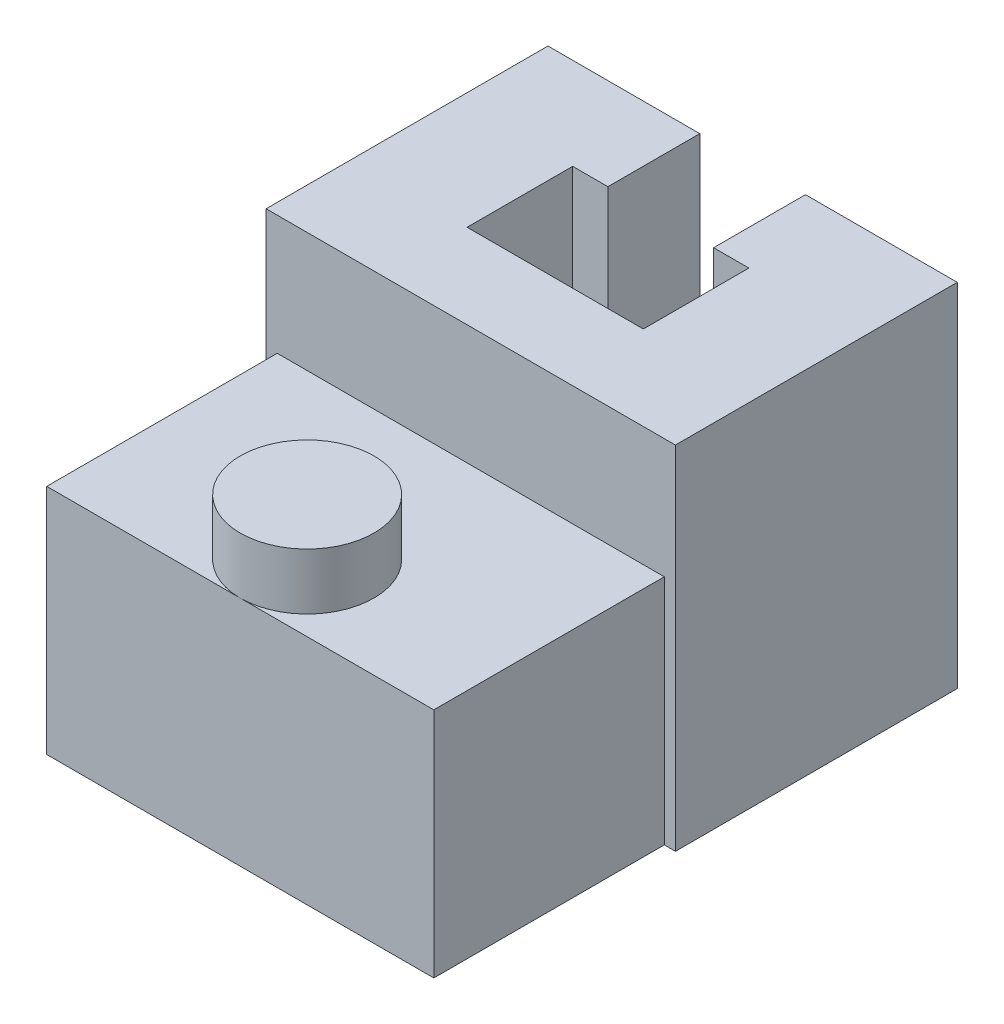
SolidWorks part; units mm, degrees
ref_plane "Front Plane" through (0, 0, 0) normal (0, 0, 1) x (1, 0, 0)
ref_plane "Top Plane" through (0, 0, 0) normal (0, 1, 0) x (1, 0, 0)
ref_plane "Right Plane" through (0, 0, 0) normal (1, 0, 0) x (0, 0, -1)
sketch "Sketch1" plane through (0, 0, 0) normal (0, 1, 0) x (1, 0, 0)
  line L0 (16.7299, 28.3015) -> (16.7299, -9.7985)
  line L1 (16.7299, -9.7985) -> (80.3315, -9.7985)
  line L2 (80.3315, -9.7985) -> (80.3315, 28.3015)
  line L3 (80.3315, 28.3015) -> (67.6061, 28.3015)
  line L4 (67.6061, 28.3015) -> (67.6061, 61.4485)
  line L5 (16.7299, 28.3015) -> (29.4553, 28.3015)
  line L6 (29.4553, 28.3015) -> (29.4553, 61.4485)
  line L7 (29.4553, 61.4485) -> (-25.3325, 61.4485)
  line L8 (-25.3325, 61.4485) -> (-25.3325, -40.2785)
  line L9 (-25.3325, -40.2785) -> (122.3939, -40.2785)
  line L10 (122.3939, -40.2785) -> (122.3939, 61.4485)
  line L11 (122.3939, 61.4485) -> (67.6061, 61.4485)
extrude "Boss-Extrude1" add sketch "Sketch1" against normal blind 127
sketch "Sketch2" plane through (0, -127, 0) normal (0, -1, 0) x (1, 0, 0)
  line L1 (-25.3325, 40.2785) -> (122.3939, 40.2785) construction
  line L2 (-21.3193, 40.2785) -> (-21.3193, 123.4635)
  line L3 (-21.3193, 123.4635) -> (118.3807, 123.4635)
  line L4 (118.3807, 123.4635) -> (118.3807, 40.2785)
  line L5 (118.3807, 40.2785) -> (-21.3193, 40.2785)
  point P8 (0, 0)
  point P9 (0, 0)
extrude "Boss-Extrude2" add sketch "Sketch2" against normal blind 83.82
sketch "Sketch3" plane through (0, -43.18, 0) normal (0, 1, 0) x (1, 0, 0)
  circle A0 centre (48.5307, -99.3335) radius 24.13
extrude "Boss-Extrude3" add sketch "Sketch3" along normal blind 20.32
